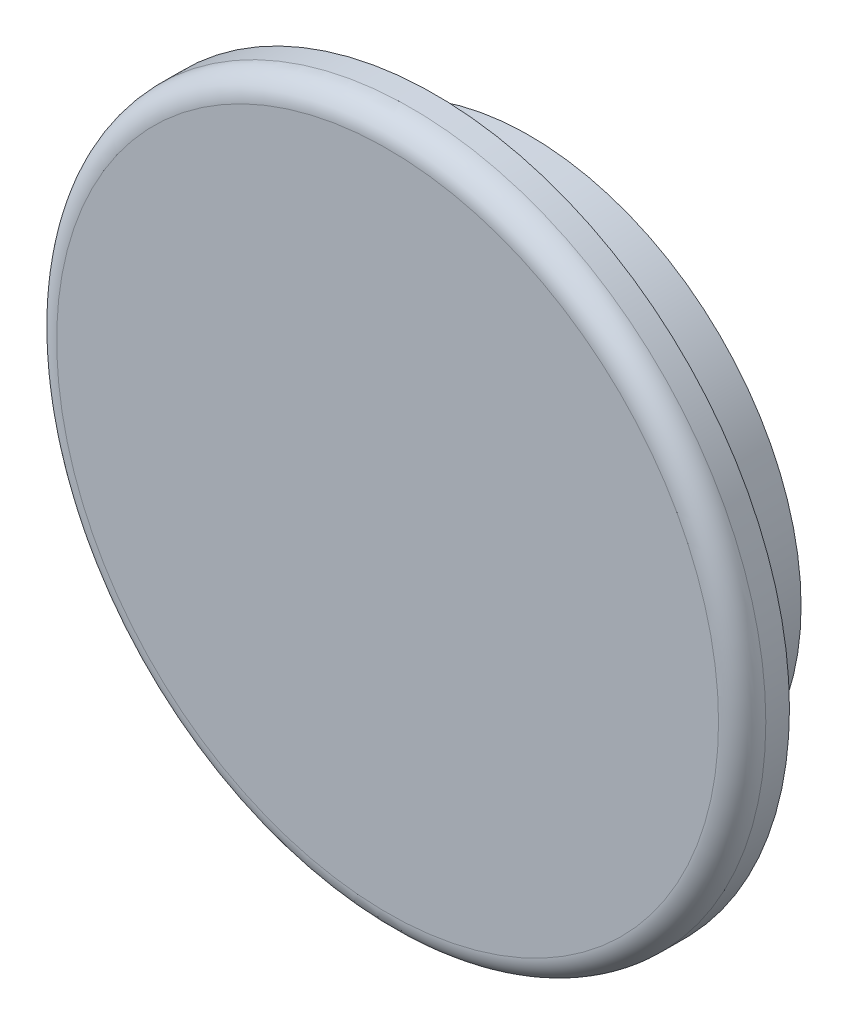
SolidWorks part; units mm, degrees
material "ABS"
ref_plane "X-Y Datum" through (0, 0, 0) normal (0, 0, 1) x (1, 0, 0)
ref_plane "X-Z Datum" through (0, 0, 0) normal (0, 1, 0) x (1, 0, 0)
ref_plane "Y-Z Datum" through (0, 0, 0) normal (1, 0, 0) x (0, 0, -1)
sketch "Sketch1" plane through (0, 0, 0) normal (0, 0, 1) x (1, 0, 0)
  circle A0 centre (0, 0) radius 6 construction
  circle A1 centre (0, 0) radius 5.746
  dimension "D1" = 12
  dimension "D2" = 0.254
extrude "Boss-Extrude1" add sketch "Sketch1" along normal blind 2
sketch "Sketch2" plane through (0, 0, 2) normal (0, 0, 1) x (1, 0, 0)
  circle A0 centre (0, 0) radius 7.5
  dimension "D1" = 15
extrude "Boss-Extrude2" add sketch "Sketch2" along normal blind 1
fillet "Fillet1" radius 0.5 1 edges at (7.5, 0, 3)
